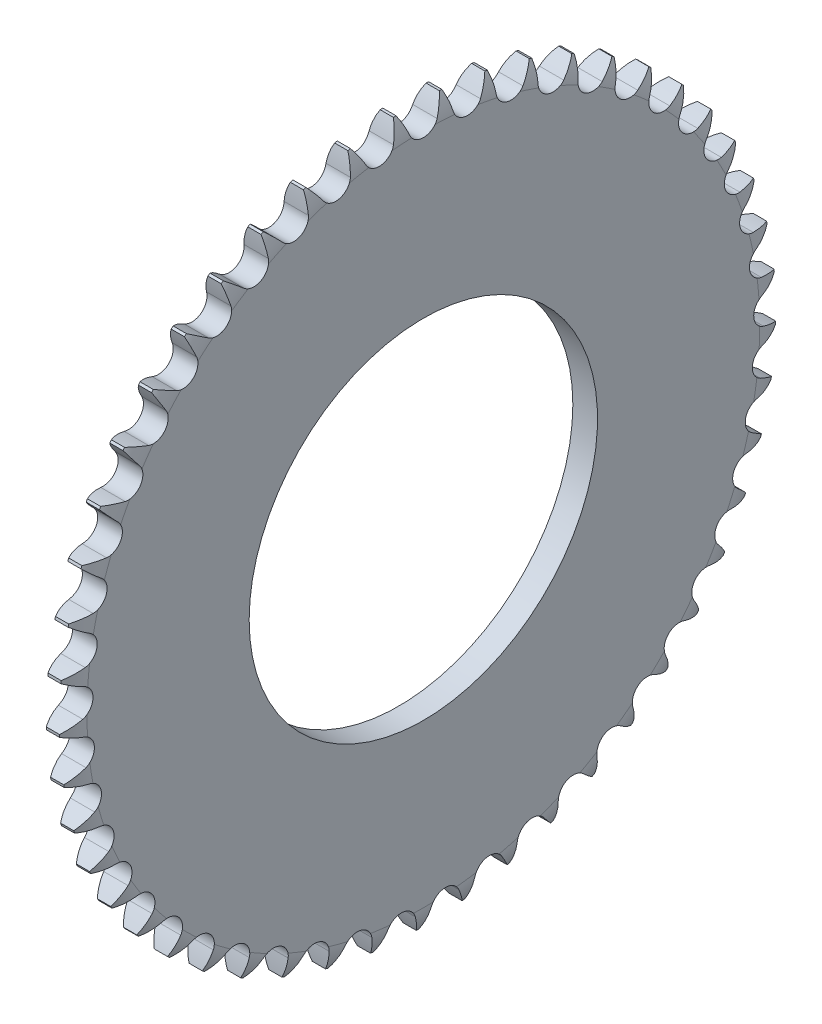
SolidWorks part; units mm, degrees
ref_plane "Plane1" through (0, 0, 0) normal (0, 0, 1) x (1, 0, 0)
ref_plane "Plane2" through (0, 0, 0) normal (0, 1, 0) x (1, 0, 0)
ref_plane "Plane3" through (0, 0, 0) normal (1, 0, 0) x (0, 0, -1)
sketch "Clipboard" plane through (0, 0, 0) normal (0, 1, 0) x (1, 0, 0)
  line L0 (0, 0) -> (6.249, -7.1886)
  line L1 (-15, 0) -> (100, 0) construction
  line L2 (0, 0) -> (-0.8203, 0.9272)
  line L3 (0, 0) -> (-8.8973, 3.4006)
  line L4 (0, 0) -> (2.0338, 2.3396)
  line L5 (0, 0) -> (-46.8476, -17.4728)
  line L6 (0, 0) -> (-4.4098, -2.9753)
  line L7 (-0.8203, 0.9272) -> (31.3194, 39.2298)
  line L8 (-76.2, 38.1) -> (-70.8, 38.1)
  line L9 (-73.3242, 40.7328) -> (-72.926, 40.7699)
  line L10 (-73.4529, 9.1872) -> (-63.2129, 9.1872)
  circle A0 centre (0, 0) radius 3.175
  circle A1 centre (0, 0) radius 37.5
  circle A2 centre (0, 0) radius 37.5
  dimension "Dr" = 6.35
  dimension "MHD" = 75
  dimension "Hub_dia" = 75
  dimension "Num_teeth" = 49
  dimension "Pitch" = 9.525
  dimension "Width" = 3.1
  dimension "Side_relief" = 1.238
  dimension "Side_radius" = 9.525
  dimension "Overall_len" = 50
  dimension "Show_teeth" = 49
  dimension "Thickness" = 5.3196
  dimension "OAL" = 50.0005
  dimension "T_dim" = 5.4
  dimension "Fillet_rad" = 0.4
  dimension "Face_width" = 5.32
  dimension "Num_strands" = 1
  dimension "Transv_pitch" = 10.24
  dimension "Plate_wid" = 8.26
sketch "BasProSke" plane through (0, 0, 0) normal (0, 1, 0) x (1, 0, 0)
  line L0 (-10, 0) -> (60, 0) construction
  line L1 (0, 0) -> (0, 72.4148)
  line L2 (0, 0) -> (5.3196, 0)
  line L3 (5.3196, 0) -> (5.3196, 72.4148)
  line L4 (4.0816, 77.1106) -> (1.238, 77.1106)
  arc A0 (0, 72.4148) -> (1.238, 77.1106) centre (9.525, 72.4148) cw
  arc A1 (5.3196, 72.4148) -> (4.0816, 77.1106) centre (-4.2054, 72.4148) ccw
  dimension "Thickness" = 5.3196
  dimension "D1" = 9.525
  dimension "G1" = 1.238
  dimension "G2" = 1.238
  dimension "Diameter" = 154.2213
revolve "Base-Revolve" add sketch "BasProSke" angle 360 about L0
sketch "TooCutSke" plane through (0, 0, 0) normal (1, 0, 0) x (0, 0, -1)
  line L0 (0, 74.3643) -> (2.9954, 73.2193) construction
  line L1 (0, 0) -> (0, 107) construction
  line L2 (0, 74.3643) -> (-10, 74.3643) construction
  line L3 (0, 74.3643) -> (-2.9954, 73.2193) construction
  arc A0 (2.9954, 73.2193) -> (4.9121, 77.455) centre (39.296, 59.3441) cw
  arc A1 (2.9954, 73.2193) -> (-2.9954, 73.2193) centre (0, 74.3643) cw
  arc A2 (-2.9954, 73.2193) -> (-4.9121, 77.455) centre (-39.296, 59.3441) ccw
  arc A3 (4.9121, 77.455) -> (-4.9121, 77.455) centre (0, 0) ccw
  dimension "R1" = 3.2067
  dimension "R2" = 38.862
  dimension "Overcut" = 77.6106
  dimension "Seat_radius" = 74.3643
  dimension "X" = 138.163
extrude "ToothCut" cut sketch "TooCutSke" along normal through all
pattern_circular "TeethCuts" count 49 every 7.347 about axis through (-10, 0, 0) along (1, 0, 0) of "ToothCut"
sketch "HubNeaOneSke" plane through (0, 0, 0) normal (-1, 0, 0) x (0, 0, 1)
  circle A0 centre (0, 0) radius 37.5
  dimension "Diameter" = 75
extrude "HubNearOne" [suppressed] add sketch "HubNeaOneSke" along normal blind 44.6809
fillet "HubNearOneFillet" [suppressed] radius 0.4
sketch "HubNeaBotSke" plane through (0, 0, 0) normal (-1, 0, 0) x (0, 0, 1)
  circle A0 centre (0, 0) radius 37.5
  dimension "Diameter" = 75
extrude "HubNearBoth" [suppressed] add sketch "HubNeaBotSke" along normal blind 22.3405
fillet "HubNearBothFillet" [suppressed] radius 0.4
ref_plane "FarPln" through (5.3196, 0, 0) normal (1, 0, 0) x (0, 0, -1)
sketch "HubFarSke" plane through (5.3196, 0, 0) normal (1, 0, 0) x (0, 0, -1)
  circle A0 centre (0, 0) radius 37.5
  dimension "Diameter" = 75
extrude "HubFar" [suppressed] add sketch "HubFarSke" along normal blind 22.3405
fillet "HubFarFillet" [suppressed] radius 0.4
sketch "BorSke" plane through (0, 0, 0) normal (1, 0, 0) x (0, 0, -1)
  circle A0 centre (0, 0) radius 37.5
  dimension "Diameter" = 75
extrude "Bore" cut sketch "BorSke" along normal mid plane 100.001
sketch "KeySke" plane through (0, 0, 0) normal (1, 0, 0) x (0, 0, -1)
  line L0 (-10, 0) -> (-10, 42.9)
  line L1 (-10, 42.9) -> (10, 42.9)
  line L2 (10, 42.9) -> (10, 0)
  line L3 (0, 0) -> (0, 34) construction
  line L4 (-10, 0) -> (10, 0)
  dimension "Offset" = 42.9
  dimension "Width" = 20
extrude "Keyway" [suppressed] cut sketch "KeySke" along normal mid plane 100.001
pattern_circular "Keyway2" [suppressed] count 2 every 90 about axis through (-10, 0, 0) along (1, 0, 0)
equation "' \"Pitch@Clipboard\" = 12.7"
equation "' \"Num_strands@Clipboard\" = 1"
equation "' \"Num_teeth@Clipboard\" = 9"
equation "' \"Hub_dia@Clipboard\" = 50"
equation "' \"Overall_len@Clipboard\" = 3"
equation "' \"Diameter@BorSke\" = 12"
equation "' \"T_dim@Clipboard\" = 1"
equation "' \"Width@KeySke\" = 2"
equation "' \"Dr@Clipboard\" = 8.51"
equation "' \"Face_width@Clipboard\" = 7.2"
equation "' \"Side_radius@Clipboard\" = 12.7"
equation "' \"Side_relief@Clipboard\" = 1.27"
equation "' \"Transv_pitch@Clipboard\" = 13.92"
equation "' \"Show_teeth@Clipboard\" = 9"
equation "' \"Fillet_rad@Clipboard\" = 0.6"
equation "' \"Plate_wid@Clipboard\" = 11.8"
equation "\"Num_teeth@Clipboard\" = int( \"Num_teeth@Clipboard\" )"
equation "\"Num_teeth@Clipboard\" = ((sgn( \"Num_teeth@Clipboard\" - 5.0)+1)*( \"Num_teeth@Clipboard\" - 5.0))/2 +5.0"
equation "\"Num_teeth@Clipboard\" = ((sgn( \"Num_teeth@Clipboard\" - 200.0)-1)*( \"Num_teeth@Clipboard\" - 200.0))/-2 +200.0"
equation "\"MHD@Clipboard\" = \"Pitch@Clipboard\" * (1.0 / tan(3.14159265 / \"Num_teeth@Clipboard\" )) - 1.04 * \"Plate_wid@Clipboard\" - 0.76"
equation "\"Thickness@Clipboard\"  = \"Face_width@Clipboard\" + (\"Num_strands@Clipboard\" - 1) * \"Transv_pitch@Clipboard\""
equation "\"OAL@Clipboard\" = \"Thickness@Clipboard\" + 2 * \"Fillet_rad@Clipboard\" + 1"
equation "\"MHD@Clipboard\" = ((sgn( \"MHD@Clipboard\" - \"Hub_dia@Clipboard\" )-1)*( \"MHD@Clipboard\" - \"Hub_dia@Clipboard\" ))/-2+ \"Hub_dia@Clipboard\""
equation "\"OAL@Clipboard\" = ((sgn( \"OAL@Clipboard\" - \"Overall_len@Clipboard\" )+1)*( \"OAL@Clipboard\" - \"Overall_len@Clipboard\" ))/2 + \"Overall_len@Clipboard\" + 0.0005"
equation "\"Num_teeth@TeethCuts\" = int( \"Show_teeth@Clipboard\" ) + 1"
equation "\"Num_teeth@TeethCuts\" = ((sgn( \"Num_teeth@TeethCuts\" - \"Num_teeth@Clipboard\" )-1)*( \"Num_teeth@TeethCuts\" - \"Num_teeth@Clipboard\" ))/-2+ \"Num_teeth@Clipboard\""
equation "\"Num_teeth@TeethCuts\" = ((sgn( \"Num_teeth@TeethCuts\" - 2.0)+1)*( \"Num_teeth@TeethCuts\" - 2.0))/2 +2.0"
equation "\"Angle@TeethCuts\" = 360.0 / \"Num_teeth@Clipboard\""
equation "\"Seat_radius@TooCutSke\" = ( \"Pitch@Clipboard\" / 2.0) / sin(3.14159265 / \"Num_teeth@Clipboard\" ) - \"Dr@Clipboard\" / 2.0 + \"Dr@Clipboard\" * 0.505"
equation "\"R1@TooCutSke\"  = \"Dr@Clipboard\" * 0.505"
equation "\"X@TooCutSke\" = 140.0 - (90.0 / \"Num_teeth@Clipboard\")"
equation "\"R2@TooCutSke\" = 0.12 * \"Dr@Clipboard\" * ( \"Num_teeth@Clipboard\" + 2.0)"
equation "\"Overcut@TooCutSke\" = 0.5 + 0.625 * \"Pitch@Clipboard\" - 0.5 * \"Dr@Clipboard\"  +  \"Pitch@Clipboard\" / 2.0 / sin(3.14159265 / \"Num_teeth@Clipboard\" )"
equation "\"Diameter@BasProSke\" = 2.0 * ( 0.625 * \"Pitch@Clipboard\" - 0.5 * \"Dr@Clipboard\"  +  \"Pitch@Clipboard\" / 2.0 / sin(3.14159265 / \"Num_teeth@Clipboard\" ))"
equation "\"Thickness@BasProSke\"  = \"Thickness@Clipboard\""
equation "\"G1@BasProSke\" =  \"Side_relief@Clipboard\""
equation "\"G2@BasProSke\" =  \"Side_relief@Clipboard\""
equation "\"D1@BasProSke\" =  \"Side_radius@Clipboard\""
equation "\"Diameter@HubNeaOneSke\" = \"MHD@Clipboard\""
equation "\"Length@HubNearOne\" = \"OAL@Clipboard\" - \"Thickness@BasProSke\""
equation "\"Diameter@HubNeaBotSke\" = \"MHD@Clipboard\""
equation "\"Length@HubNearBoth\" = ( \"OAL@Clipboard\" - \"Thickness@BasProSke\" ) / 2.0"
equation "\"D1@HubNearOneFillet\" = \"Fillet_rad@Clipboard\""
equation "\"D1@HubNearBothFillet\" = \"Fillet_rad@Clipboard\""
equation "\"Thickness@FarPln\" = \"Thickness@BasProSke\""
equation "\"Diameter@HubFarSke\" = \"MHD@Clipboard\""
equation "\"Length@HubFar\" = ( \"OAL@Clipboard\" - \"Thickness@BasProSke\" ) / 2.0"
equation "\"D1@HubFarFillet\" = \"Fillet_rad@Clipboard\""
equation "\"D1@Bore\" = \"OAL@Clipboard\" * 2.0"
equation "\"D1@Keyway\" = \"OAL@Clipboard\" * 2.0"
equation "\"Offset@KeySke\" = \"T_dim@Clipboard\" + \"Diameter@BorSke\" / 2.0"
